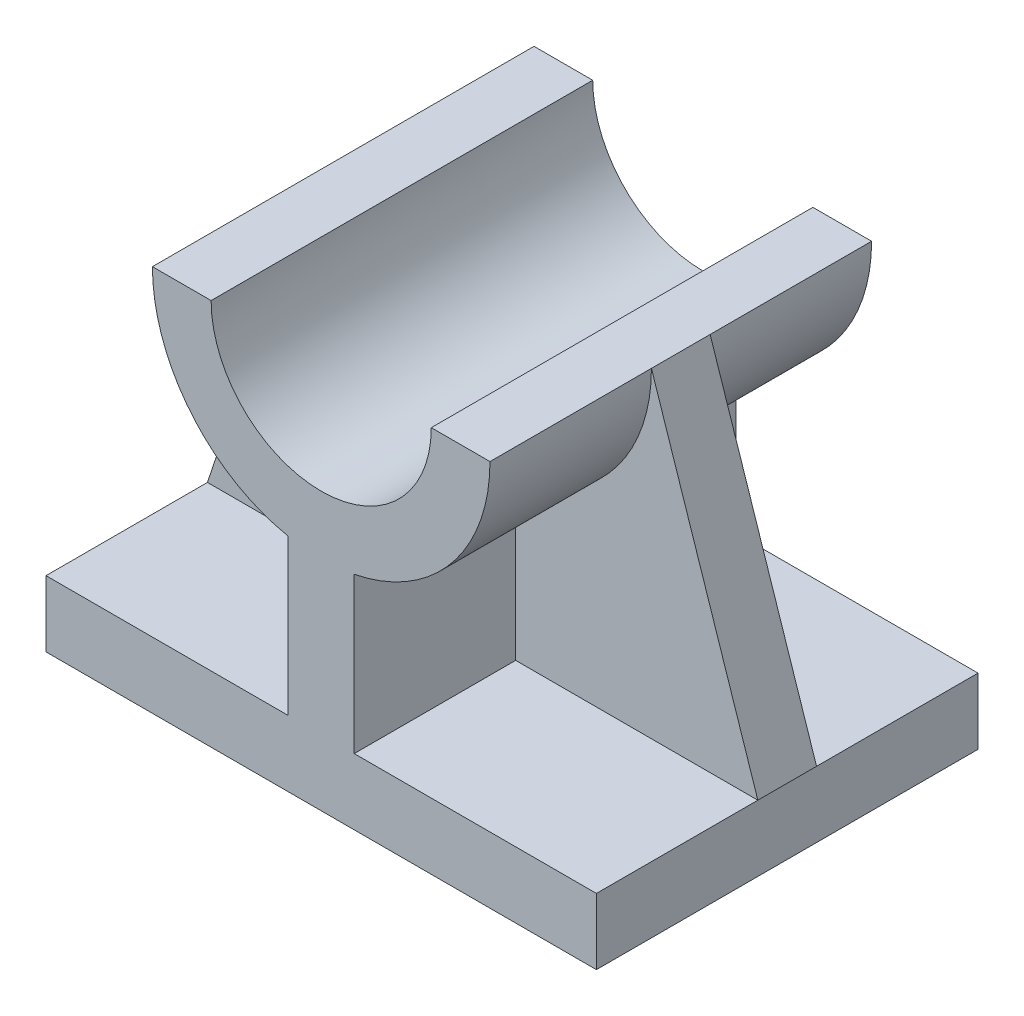
SolidWorks part; units mm, degrees
ref_plane "Front Plane" through (0, 0, 0) normal (0, 0, 1) x (1, 0, 0)
ref_plane "Top Plane" through (0, 0, 0) normal (0, 1, 0) x (1, 0, 0)
ref_plane "Right Plane" through (0, 0, 0) normal (1, 0, 0) x (0, 0, -1)
sketch "Sketch3" plane through (0, 0, 0) normal (0, 0, 1) x (1, 0, 0)
  line L0 (0, 36) -> (0, 31.3929) construction
  line L1 (-37.5, -27.3214) -> (-4.5, -27.3214)
  line L2 (-37.5, -27.3214) -> (-37.5, -36.3214)
  line L3 (-37.5, -36.3214) -> (37.5, -36.3214)
  line L4 (37.5, -27.3214) -> (37.5, -36.3214)
  line L5 (-23, 16.3929) -> (-15, 16.3929)
  line L6 (4.5, -27.3214) -> (4.5, -6.1626)
  line L7 (-4.5, -27.3214) -> (-4.5, -6.1626)
  line L8 (0, 1.3929) -> (0, -68.3036) construction
  line L9 (15, 16.3929) -> (23, 16.3929)
  line L10 (4.5, -27.3214) -> (37.5, -27.3214)
  arc A0 (-15, 16.3929) -> (15, 16.3929) centre (0, 16.3929) ccw
  arc A1 (-23, 16.3929) -> (-4.5, -6.1626) centre (0, 16.3929) ccw
  arc A2 (4.5, -6.1626) -> (23, 16.3929) centre (0, 16.3929) ccw
  dimension "D3" = 30
  dimension "D4" = 46
  dimension "D1" = 9
  dimension "D2" = 75
  dimension "D5" = 37.5
  dimension "D6" = 4.5
extrude "Boss-Extrude2" add sketch "Sketch3" along normal mid plane 52
sketch "Sketch5" plane through (0, 0, 0) normal (0, 0, 1) x (1, 0, 0)
  line L0 (23, 16.3929) -> (37.5, -27.3214)
  line L1 (23, 16.3929) -> (15, 16.3929) construction
  arc A0 (4.5, -6.1626) -> (23, 16.3929) centre (0, 16.3929) ccw construction
rib "Rib1" sketch "Sketch5" sketch "Sketch5" thickness 8 extrusion direction parallel to sketch draft on no parameters "D1"=8
mirror "Mirror1" about plane through (0, 0, 0) normal (1, 0, 0) of "Rib1"
